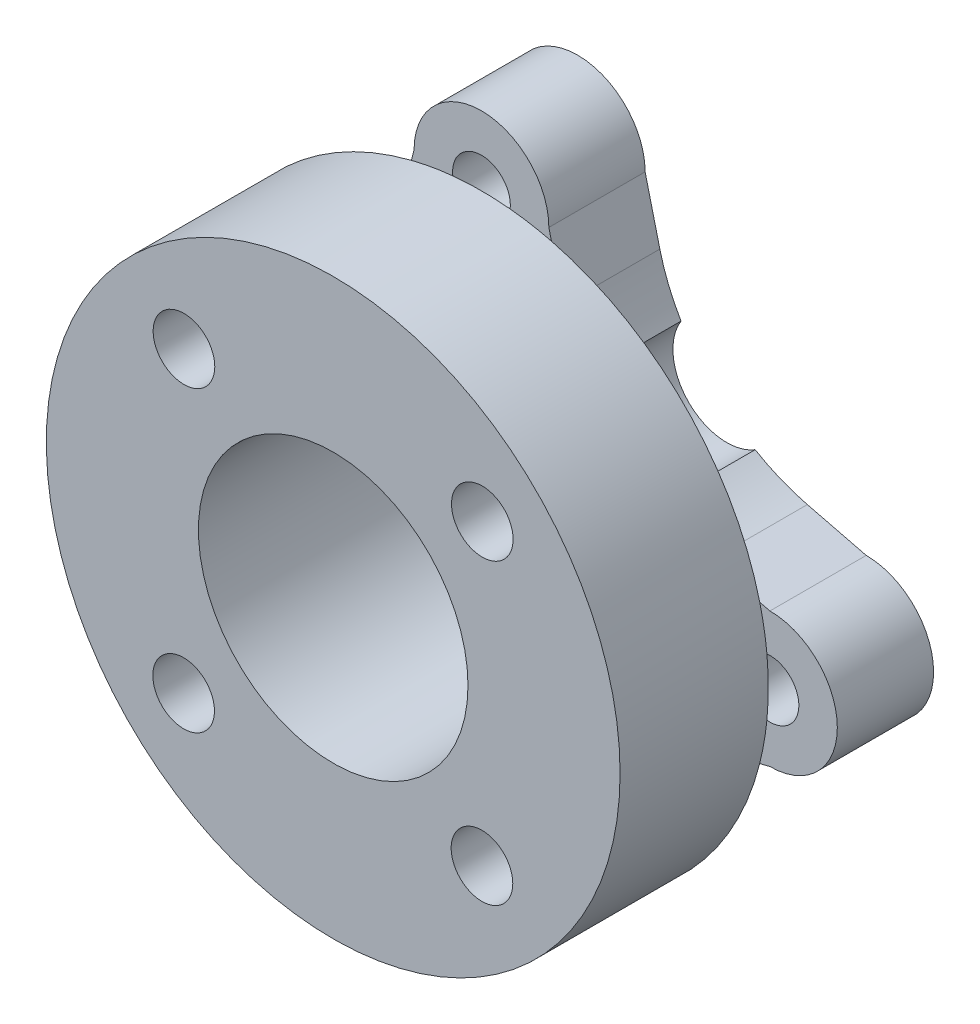
SolidWorks part; units mm, degrees
ref_plane "Front Plane" through (0, 0, 0) normal (0, 0, 1) x (1, 0, 0)
ref_plane "Top Plane" through (0, 0, 0) normal (0, 1, 0) x (1, 0, 0)
ref_plane "Right Plane" through (0, 0, 0) normal (1, 0, 0) x (0, 0, -1)
sketch "Sketch1" plane through (0, 0, 0) normal (0, 0, 1) x (1, 0, 0)
  line L1 (-3.487, 14.9951) -> (-4.2519, 11.9044)
  line L5 (3.5119, 14.9951) -> (4.2768, 11.9045)
  line L7 (14.9951, -3.5119) -> (11.9165, -4.2738)
  line L8 (14.9951, 3.487) -> (11.9374, 4.2437)
  line L9 (-3.5119, -14.9951) -> (-4.2819, -11.8837)
  line L10 (3.487, -14.9951) -> (4.241, -11.9485)
  line L11 (-14.9951, 3.5119) -> (-11.8717, 4.2849)
  line L12 (-14.9951, -3.487) -> (-11.9156, -4.2491)
  line L15 (-2.1044, -6.677) -> (-1.6771, -6.7827)
  line L16 (6.6355, -2.2721) -> (6.7827, -1.6771)
  line L18 (2.0896, 6.6807) -> (1.6771, 6.7827)
  circle A1 centre (0.0126, -0.0045) radius 7.0003
  circle A3 centre (0.0124, 14.9951) radius 1.5
  arc A4 (3.5119, 14.9951) -> (-3.487, 14.9951) centre (0.0124, 14.9951) ccw
  arc A5 (14.9951, -3.5119) -> (14.9951, 3.487) centre (14.9951, -0.0124) ccw
  circle A6 centre (14.9951, -0.0124) radius 1.5
  arc A7 (-3.5119, -14.9951) -> (3.487, -14.9951) centre (-0.0124, -14.9951) ccw
  circle A8 centre (-0.0124, -14.9951) radius 1.5
  arc A9 (-14.9951, 3.5119) -> (-14.9951, -3.487) centre (-14.9951, 0.0124) ccw
  circle A10 centre (-14.9951, 0.0124) radius 1.5
  arc A11 (-6.9733, 7.1512) -> (-7.1309, 6.9939) centre (0.0126, -0.0045) ccw
  circle A12 centre (0.0126, -0.0045) radius 10.0003 construction
  arc A13 (6.9805, -7.1777) -> (7.1659, -6.9928) centre (0.0126, -0.0045) ccw
  arc A14 (7.1762, 6.9733) -> (6.9984, 7.1514) centre (0.0126, -0.0045) ccw
  arc A15 (-7.1527, -6.9805) -> (-6.9883, -7.1454) centre (0.0126, -0.0045) ccw
  arc A16 (4.2768, 11.9045) -> (6.9984, 7.1514) centre (13.9839, 14.3069) ccw
  arc A17 (7.1762, 6.9733) -> (11.9374, 4.2437) centre (14.3396, 13.9509) ccw
  arc A18 (11.9165, -4.2738) -> (7.1659, -6.9928) centre (14.319, -13.9809) ccw
  arc A19 (6.9805, -7.1777) -> (4.241, -11.9485) centre (13.9481, -14.3507) ccw
  arc A20 (-4.2819, -11.8837) -> (-6.9883, -7.1454) centre (-13.9891, -14.2861) ccw
  arc A21 (-7.1527, -6.9805) -> (-11.9156, -4.2491) centre (-14.3177, -13.9563) ccw
  arc A22 (-11.8717, 4.2849) -> (-7.1309, 6.9939) centre (-14.2741, 13.992) ccw
  arc A23 (-6.9733, 7.1512) -> (-4.2519, 11.9044) centre (-13.9591, 14.3066) ccw
  point P28 (0, 0)
  point P30 (0, 0)
  point P40 (8.6352, 5.0609)
  point P43 (8.6241, -5.0887)
  point P46 (5.0603, -8.6374)
  point P51 (-8.6118, -5.0667)
  dimension "D1" = 4
  dimension "D2" = 3
  dimension "D3" = 10
extrude "Boss-Extrude1" add sketch "Sketch1" along normal blind 5 contours A23 A11 A22 L11 A9 L12 A21 A15 A20 L9 A7 L10 A19 A13 A18 L7 A5 L8 A17 A14 A16 L5 A4 L1 A10 A8 A6 A3 A1
sketch "Sketch2" plane through (0, 0, 5) normal (0, 0, 1) x (1, 0, 0)
  circle A5 centre (0.0126, -0.0045) radius 14.9
  circle A6 centre (0.0126, -0.0045) radius 7.0003 construction
  circle A7 centre (0.0126, -0.0045) radius 7.0003
extrude "Boss-Extrude2" add sketch "Sketch2" along normal blind 7.7
sketch "Sketch3" plane through (0, 0, 12.7) normal (0, 0, 1) x (1, 0, 0)
  circle A1 centre (7.7554, 7.7384) radius 1.6
  circle A2 centre (7.7384, -7.7554) radius 1.6
  circle A3 centre (-7.7554, -7.7384) radius 1.6
  circle A4 centre (-7.7384, 7.7554) radius 1.6
  point P13 (0, 0)
  dimension "D1" = 4
extrude "Cut-Extrude1" cut sketch "Sketch3" against normal through all
sketch "Sketch4" plane through (0, 0, 0) normal (0, 0, -1) x (-1, 0, 0)
  circle A0 centre (-7.7554, 7.7384) radius 2.8
  circle A1 centre (7.7384, 7.7554) radius 2.8
  circle A2 centre (7.7554, -7.7384) radius 2.8
  circle A3 centre (-7.7384, -7.7554) radius 2.8
  point P12 (0, 0)
  dimension "D1" = 4
extrude "Cut-Extrude2" cut sketch "Sketch4" against normal up to surface (5 mm away) up to face at (8.5867, 8.5611, 5)
